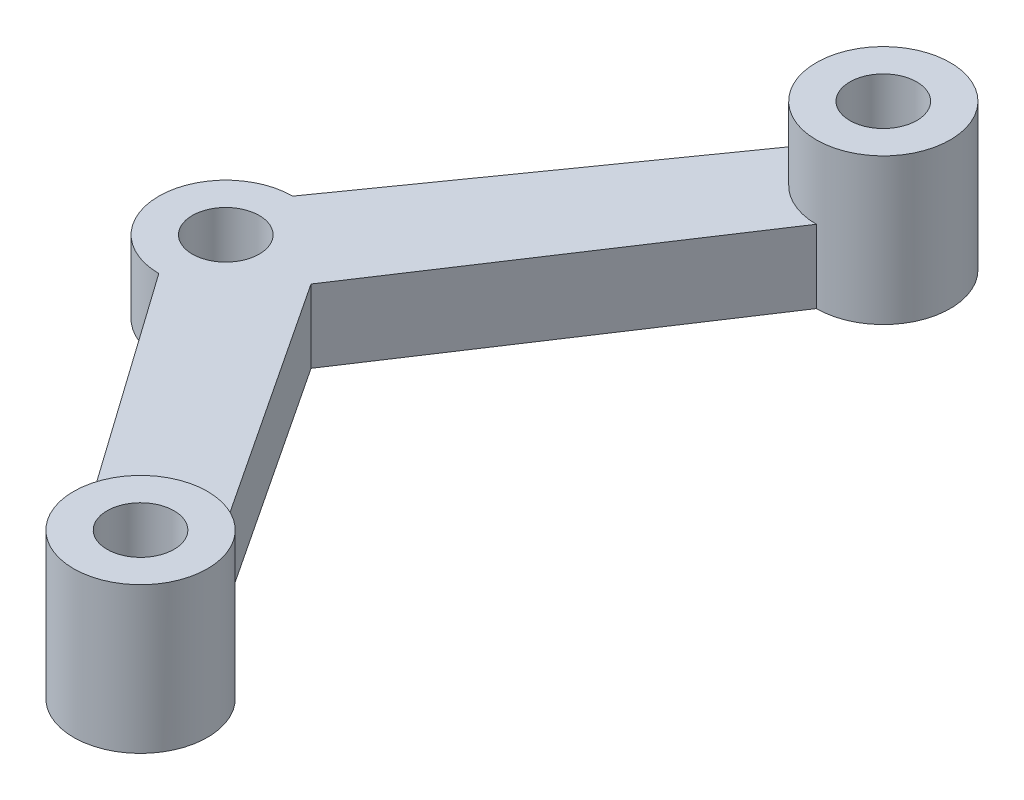
SolidWorks part; units mm, degrees
ref_plane "Front Plane" through (0, 0, 0) normal (0, 0, 1) x (1, 0, 0)
ref_plane "Top Plane" through (0, 0, 0) normal (0, 1, 0) x (1, 0, 0)
ref_plane "Right Plane" through (0, 0, 0) normal (1, 0, 0) x (0, 0, -1)
sketch "Sketch1" plane through (0, 0, 0) normal (0, 1, 0) x (1, 0, 0)
  line L1 (-15.25, -15.25) -> (15.25, -15.25) construction
  line L2 (-15.25, -15.25) -> (-15.25, 15.25) construction
  line L3 (-15.25, 15.25) -> (15.25, 15.25) construction
  line L4 (15.25, -15.25) -> (15.25, 15.25) construction
  line L5 (-15.25, -15.25) -> (15.25, 15.25) construction
  line L6 (-15.25, 15.25) -> (15.25, -15.25) construction
  point P0 (0, 0)
  dimension "D1" = 30.5
sketch "Sketch2" plane through (0, 0, 0) normal (0, 1, 0) x (1, 0, 0)
  line L1 (-23, -16) -> (23, -16) construction
  line L2 (-23, -16) -> (-23, 16) construction
  line L3 (-23, 16) -> (23, 16) construction
  line L4 (23, -16) -> (23, 16) construction
  line L5 (-23, -16) -> (23, 16) construction
  line L6 (-23, 16) -> (23, -16) construction
  line L7 (-23, 0) -> (23, 0) construction
  line L9 (-27, -2.75) -> (-17.9878, -15.509)
  line L10 (-15.25, -12.5) -> (-23.5, 0)
  line L11 (-15.25, 12.5) -> (-23.5, 0)
  line L12 (-17.9878, 15.509) -> (-27, 2.75)
  arc A0 (-27, 2.75) -> (-27, -2.75) centre (-27, 0) ccw
  circle A1 centre (-27, 0) radius 1.375
  circle A2 centre (-15.25, 15.25) radius 1.375
  arc A3 (-15.25, 12.5) -> (-17.9878, 15.509) centre (-15.25, 15.25) ccw
  circle A4 centre (-15.25, -15.25) radius 1.375
  arc A5 (-17.9878, -15.509) -> (-15.25, -12.5) centre (-15.25, -15.25) ccw
  point P0 (0, 0)
  point P12 (-21.9147, 0)
  dimension "D4" = 5.5
  dimension "D5" = 2.75
  dimension "D6" = 2.75
  dimension "D7" = 5.5
  dimension "D1" = 32
  dimension "D2" = 46
  dimension "D3" = 4
  dimension "D8" = 3.5
  dimension "D9" = 15.6209
extrude "Boss-Extrude1" add sketch "Sketch2" along normal blind 3
sketch "Sketch3" plane through (0, 3, 0) normal (0, 1, 0) x (1, 0, 0)
  circle A0 centre (-15.25, 15.25) radius 1.375
  circle A1 centre (-15.25, 15.25) radius 2.75
  circle A2 centre (-15.25, -15.25) radius 2.75
  circle A3 centre (-15.25, -15.25) radius 1.375
  dimension "D1" = 2.75
  dimension "D2" = 5.5
extrude "Boss-Extrude2" add sketch "Sketch3" along normal blind 3
